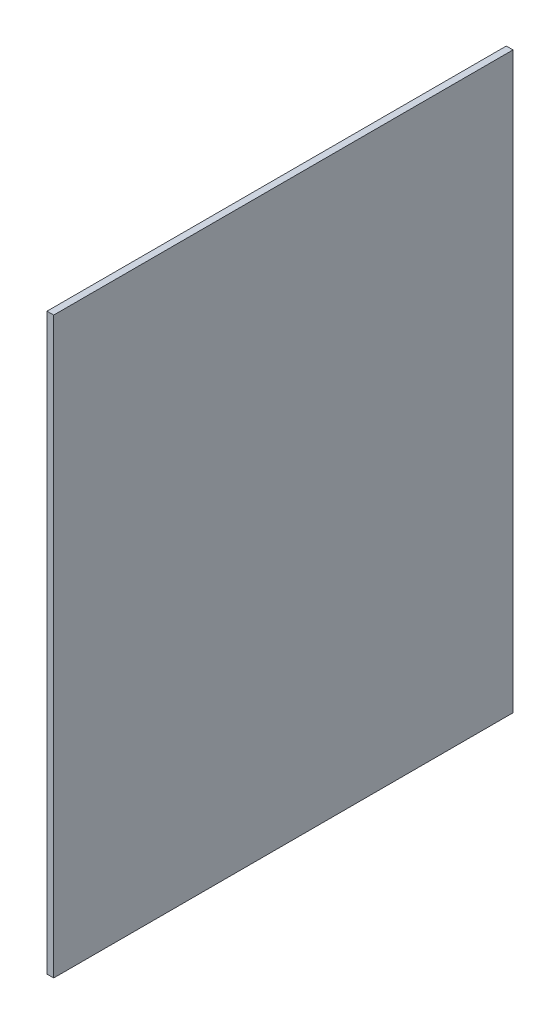
SolidWorks part; units mm, degrees
ref_plane "Front Plane" through (0, 0, 0) normal (1, 0, 0) x (0, 1, 0)
ref_plane "Top Plane" through (0, 0, 0) normal (0, 0, 1) x (0, 1, 0)
ref_plane "Right Plane" through (0, 0, 0) normal (0, 1, 0) x (-1, 0, 0)
sketch "Sketch1" plane through (0, 0, 0) normal (1, 0, 0) x (0, 1, 0)
  line L1 (-5.5454, 0) -> (248.4546, 0)
  line L2 (-5.5454, 0) -> (-5.5454, 203.2)
  line L3 (-5.5454, 203.2) -> (248.4546, 203.2)
  line L4 (248.4546, 0) -> (248.4546, 203.2)
  dimension "D1" = 203.2
  dimension "D2" = 254
extrude "Boss-Extrude1" add sketch "Sketch1" along normal blind 2.9718
